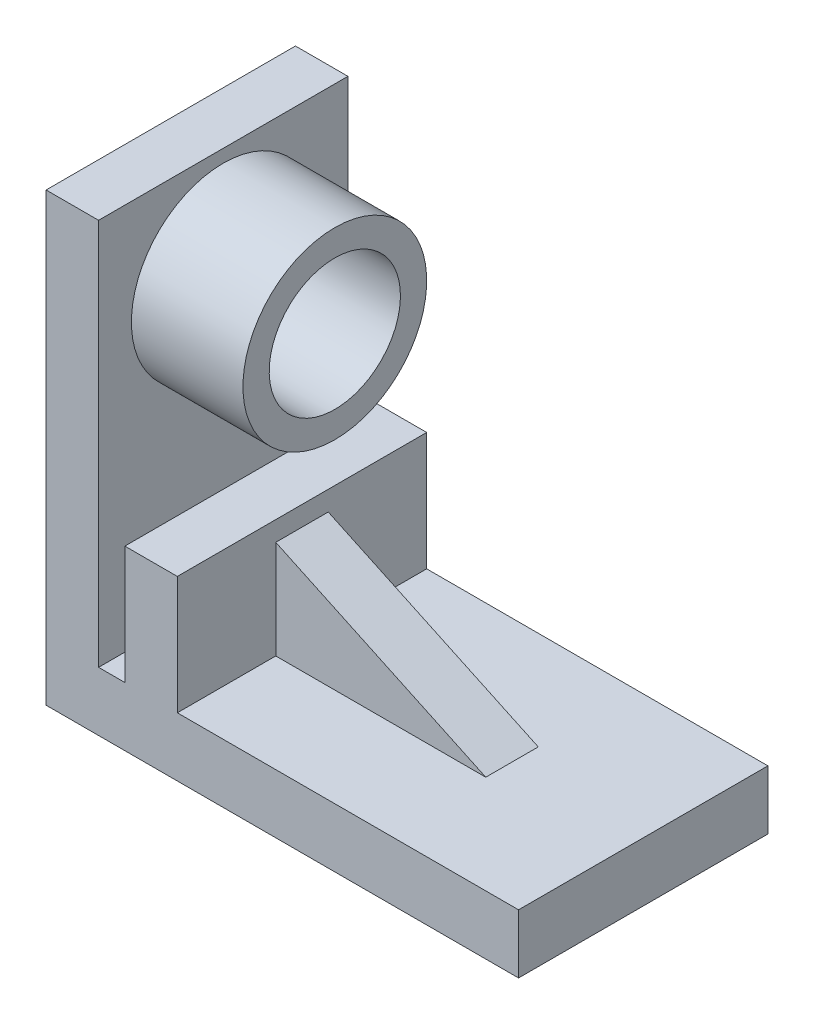
SolidWorks part; units mm, degrees
ref_plane "Front Plane" through (0, 0, 0) normal (0, 0, 1) x (1, 0, 0)
ref_plane "Top Plane" through (0, 0, 0) normal (0, 1, 0) x (1, 0, 0)
ref_plane "Right Plane" through (0, 0, 0) normal (1, 0, 0) x (0, 0, -1)
sketch "Croquis1" plane through (0, 0, 0) normal (0, 0, 1) x (1, 0, 0)
  line L0 (0, 0) -> (0, 68)
  line L1 (0, 68) -> (8, 68)
  line L2 (8, 68) -> (8, 9)
  line L3 (8, 9) -> (12, 9)
  line L4 (12, 9) -> (12, 27)
  line L5 (12, 27) -> (20, 27)
  line L6 (20, 27) -> (20, 9)
  line L7 (20, 9) -> (72, 9)
  line L8 (72, 9) -> (72, 0)
  line L9 (72, 0) -> (0, 0)
  dimension "D1" = 8
  dimension "D2" = 8
  dimension "D3" = 20
  dimension "D4" = 72
  dimension "D5" = 68
  dimension "D6" = 18
  dimension "D7" = 9
  dimension "D8" = 9
extrude "Saliente-Extruir2" add sketch "Croquis1" along normal mid plane 38
sketch "Croquis3" plane through (20, 0, 0) normal (1, 0, 0) x (0, 0, -1)
  line L0 (0, 9) -> (-4, 9)
  line L1 (-19, 9) -> (19, 9) construction
  line L2 (-4, 9) -> (-4, 24)
  line L3 (-4, 24) -> (4, 24)
  line L4 (4, 24) -> (4, 9)
  line L5 (-19, 9) -> (19, 9) construction
  line L6 (4, 9) -> (0, 9)
  dimension "D1" = 8
  dimension "D2" = 15
  dimension "D3" = 4
extrude "Saliente-Extruir3" add sketch "Croquis3" along normal blind 32
sketch "Croquis4" plane through (0, 0, 4) normal (0, 0, 1) x (1, 0, 0)
  line L0 (20, 24) -> (52, 9)
  line L1 (72, 9) -> (20, 9) construction
  line L2 (52, 9) -> (20, 9) construction
  line L3 (52, 9) -> (52, 24)
  line L4 (52, 24) -> (20, 24)
extrude "Cortar-Extruir1" cut sketch "Croquis4" against normal through all
sketch "Croquis5" plane through (8, 0, 0) normal (1, 0, 0) x (0, 0, -1)
  circle A0 centre (0, 52.0351) radius 14
  circle A1 centre (0, 52.0351) radius 10
  dimension "D1" = 28
  dimension "D2" = 20
extrude "Saliente-Extruir4" add sketch "Croquis5" along normal blind 17
